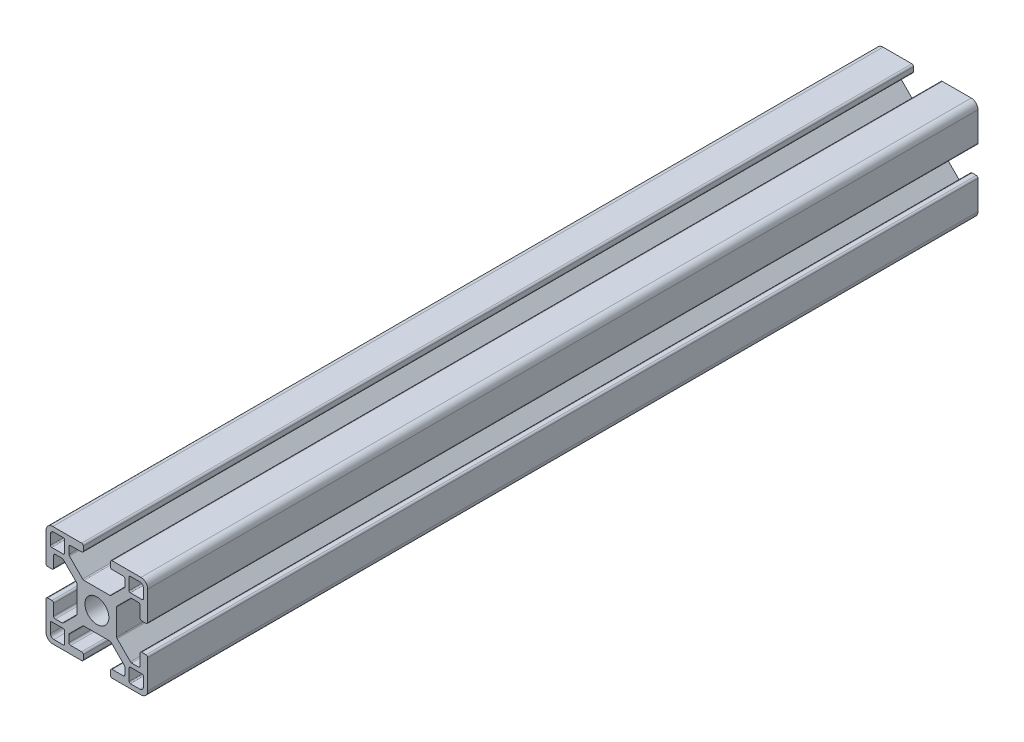
SolidWorks part; units mm, degrees
ref_plane "Front Plane" through (0, 0, 0) normal (0, 0, 1) x (1, 0, 0)
ref_plane "Top Plane" through (0, 0, 0) normal (0, 1, 0) x (1, 0, 0)
ref_plane "Right Plane" through (0, 0, 0) normal (1, 0, 0) x (0, 0, -1)
sketch "Sketch1" plane through (0, 0, 0) normal (0, 0, 1) x (1, 0, 0)
  line L0 (3.9799, -2.4733) -> (3.1981, -1.4942) construction
  line L1 (1.4942, -3.1981) -> (2.4733, -3.9799) construction
  line L2 (-2.4733, -3.9799) -> (-1.4942, -3.1981) construction
  line L3 (-3.1981, -1.4942) -> (-3.9799, -2.4733) construction
  line L4 (-3.9799, 2.4733) -> (-3.1981, 1.4942) construction
  line L5 (-1.4942, 3.1981) -> (-2.4733, 3.9799) construction
  line L6 (2.4733, 3.9799) -> (1.4942, 3.1981) construction
  line L7 (3.1981, 1.4942) -> (3.9799, 2.4733) construction
  line L8 (-12.6999, -13.6999) -> (-9.881, -13.6999)
  line L9 (-13.6999, -9.881) -> (-13.6999, -12.6999)
  line L10 (-9.88, -9.5) -> (-13.3189, -9.5)
  line L11 (-9.5, -13.3189) -> (-9.5, -9.88)
  line L12 (13.6999, -12.6999) -> (13.6999, -9.881)
  line L13 (9.881, -13.6999) -> (12.6999, -13.6999)
  line L14 (9.5, -9.88) -> (9.5, -13.3189)
  line L15 (13.3189, -9.5) -> (9.88, -9.5)
  line L16 (9.88, 9.5) -> (13.3189, 9.5)
  line L17 (9.5, 13.3189) -> (9.5, 9.88)
  line L18 (12.6999, 13.6999) -> (9.881, 13.6999)
  line L19 (13.6999, 9.881) -> (13.6999, 12.6999)
  line L20 (-13.6999, 12.6999) -> (-13.6999, 9.881)
  line L21 (-9.881, 13.6999) -> (-12.6999, 13.6999)
  line L22 (-9.5, 9.88) -> (-9.5, 13.3189)
  line L23 (-13.3189, 9.5) -> (-9.88, 9.5)
  line L24 (14.4999, -4) -> (13.2425, -4)
  line L25 (12.7425, -4.5) -> (12.7425, -7.7325)
  line L26 (12.2428, -8.25) -> (10.2602, -8.25)
  line L27 (9.9066, -8.1035) -> (5.9811, -4.178)
  line L28 (5.8347, -3.8245) -> (5.8347, -1.0125)
  line L29 (5.8347, -1.0125) -> (5.3247, -0.0625) construction
  line L30 (5.3247, -0.0625) -> (5.8347, 0.8875) construction
  line L31 (5.8347, 0.8875) -> (5.8347, 3.8245)
  line L32 (5.9811, 4.178) -> (9.9066, 8.1035)
  line L33 (10.2602, 8.25) -> (12.2428, 8.25)
  line L34 (12.7425, 7.7325) -> (12.7425, 4.5)
  line L35 (13.2425, 4) -> (14.4999, 4)
  line L36 (14.9999, 4.5) -> (14.9999, 12.9999)
  line L37 (12.9999, 14.9999) -> (4.5, 14.9999)
  line L38 (4, 14.4999) -> (4, 13.2425)
  line L39 (4.5, 12.7425) -> (7.7325, 12.7425)
  line L40 (8.25, 12.2428) -> (8.25, 10.2602)
  line L41 (8.1035, 9.9066) -> (4.178, 5.9811)
  line L42 (3.8245, 5.8347) -> (0.95, 5.8347)
  line L43 (0.95, 5.8347) -> (0, 5.3247) construction
  line L44 (0, 5.3247) -> (-0.95, 5.8347) construction
  line L45 (-0.95, 5.8347) -> (-3.8245, 5.8347)
  line L46 (-4.178, 5.9811) -> (-8.1035, 9.9066)
  line L47 (-8.25, 10.2602) -> (-8.25, 12.2428)
  line L48 (-7.7325, 12.7425) -> (-4.5, 12.7425)
  line L49 (-4, 13.2425) -> (-4, 14.4999)
  line L50 (-4.5, 14.9999) -> (-12.9999, 14.9999)
  line L51 (-14.9999, 12.9999) -> (-14.9999, 4.5)
  line L52 (-14.4999, 4) -> (-13.2425, 4)
  line L53 (-12.7425, 4.5) -> (-12.7425, 7.7325)
  line L54 (-12.2428, 8.25) -> (-10.2602, 8.25)
  line L55 (-9.9066, 8.1035) -> (-5.9811, 4.178)
  line L56 (-5.8347, 3.8245) -> (-5.8347, 0.8875)
  line L57 (-5.8347, 0.8875) -> (-5.3247, -0.0625) construction
  line L58 (-5.3247, -0.0625) -> (-5.8347, -1.0125) construction
  line L59 (-5.8347, -1.0125) -> (-5.8347, -3.8245)
  line L60 (-5.9811, -4.178) -> (-9.9066, -8.1035)
  line L61 (-10.2602, -8.25) -> (-12.2428, -8.25)
  line L62 (-12.7425, -7.7325) -> (-12.7425, -4.5)
  line L63 (-13.2425, -4) -> (-14.4999, -4)
  line L64 (-14.9999, -4.5) -> (-14.9999, -12.9999)
  line L65 (-12.9999, -14.9999) -> (-4.5, -14.9999)
  line L66 (-4, -14.4999) -> (-4, -13.2425)
  line L67 (-4.5, -12.7425) -> (-7.7325, -12.7425)
  line L68 (-8.25, -12.2428) -> (-8.25, -10.2602)
  line L69 (-8.1035, -9.9066) -> (-4.178, -5.9811)
  line L70 (-3.8245, -5.8347) -> (-0.95, -5.8347)
  line L71 (-0.95, -5.8347) -> (0, -5.3247) construction
  line L72 (0, -5.3247) -> (0.95, -5.8347) construction
  line L73 (0.95, -5.8347) -> (3.8245, -5.8347)
  line L74 (4.178, -5.9811) -> (8.1035, -9.9066)
  line L75 (8.25, -10.2602) -> (8.25, -12.2428)
  line L76 (7.7325, -12.7425) -> (4.5, -12.7425)
  line L77 (4, -13.2425) -> (4, -14.4999)
  line L78 (4.5, -14.9999) -> (12.9999, -14.9999)
  line L79 (14.9999, -12.9999) -> (14.9999, -4.5)
  line L80 (-5.8347, -1.0125) -> (-5.8347, 0.8875)
  line L81 (-0.95, 5.8347) -> (0.95, 5.8347)
  line L82 (5.8347, 0.8875) -> (5.8347, -1.0125)
  line L83 (-0.95, -5.8347) -> (0.95, -5.8347)
  arc A0 (2.4733, -3.9799) -> (3.9799, -2.4733) centre (3.1422, -3.1422) ccw construction
  arc A1 (-1.4942, -3.1981) -> (1.4942, -3.1981) centre (0, 0) ccw construction
  arc A2 (-3.9799, -2.4733) -> (-2.4733, -3.9799) centre (-3.1422, -3.1422) ccw construction
  arc A3 (-3.1981, 1.4942) -> (-3.1981, -1.4942) centre (0, 0) ccw construction
  arc A4 (-2.4733, 3.9799) -> (-3.9799, 2.4733) centre (-3.1422, 3.1422) ccw construction
  arc A5 (1.4942, 3.1981) -> (-1.4942, 3.1981) centre (0, 0) ccw construction
  arc A6 (3.9799, 2.4733) -> (2.4733, 3.9799) centre (3.1422, 3.1422) ccw construction
  arc A7 (3.1981, -1.4942) -> (3.1981, 1.4942) centre (0, 0) ccw construction
  arc A8 (-13.6999, -12.6999) -> (-12.6999, -13.6999) centre (-12.6999, -12.6999) ccw
  arc A9 (-13.3189, -9.5) -> (-13.6999, -9.881) centre (-13.3189, -9.881) ccw
  arc A10 (-9.5, -9.88) -> (-9.88, -9.5) centre (-9.88, -9.88) ccw
  arc A11 (-9.881, -13.6999) -> (-9.5, -13.3189) centre (-9.881, -13.3189) ccw
  arc A12 (12.6999, -13.6999) -> (13.6999, -12.6999) centre (12.6999, -12.6999) ccw
  arc A13 (9.5, -13.3189) -> (9.881, -13.6999) centre (9.881, -13.3189) ccw
  arc A14 (9.88, -9.5) -> (9.5, -9.88) centre (9.88, -9.88) ccw
  arc A15 (13.6999, -9.881) -> (13.3189, -9.5) centre (13.3189, -9.881) ccw
  arc A16 (9.5, 9.88) -> (9.88, 9.5) centre (9.88, 9.88) ccw
  arc A17 (9.881, 13.6999) -> (9.5, 13.3189) centre (9.881, 13.3189) ccw
  arc A18 (13.6999, 12.6999) -> (12.6999, 13.6999) centre (12.6999, 12.6999) ccw
  arc A19 (13.3189, 9.5) -> (13.6999, 9.881) centre (13.3189, 9.881) ccw
  arc A20 (14.9999, -4.5) -> (14.4999, -4) centre (14.4999, -4.5) ccw
  arc A21 (13.2425, -4) -> (12.7425, -4.5) centre (13.2425, -4.5) ccw
  arc A22 (12.2428, -8.25) -> (12.7425, -7.7325) centre (12.2428, -7.75) ccw
  arc A23 (9.9066, -8.1035) -> (10.2602, -8.25) centre (10.2602, -7.75) ccw
  arc A24 (5.8347, -3.8245) -> (5.9811, -4.178) centre (6.3347, -3.8245) ccw
  arc A25 (5.9811, 4.178) -> (5.8347, 3.8245) centre (6.3347, 3.8245) ccw
  arc A26 (10.2602, 8.25) -> (9.9066, 8.1035) centre (10.2602, 7.75) ccw
  arc A27 (12.7425, 7.7325) -> (12.2428, 8.25) centre (12.2428, 7.75) ccw
  arc A28 (12.7425, 4.5) -> (13.2425, 4) centre (13.2425, 4.5) ccw
  arc A29 (14.4999, 4) -> (14.9999, 4.5) centre (14.4999, 4.5) ccw
  arc A30 (14.9999, 12.9999) -> (12.9999, 14.9999) centre (12.9999, 12.9999) ccw
  arc A31 (4.5, 14.9999) -> (4, 14.4999) centre (4.5, 14.4999) ccw
  arc A32 (4, 13.2425) -> (4.5, 12.7425) centre (4.5, 13.2425) ccw
  arc A33 (8.25, 12.2428) -> (7.7325, 12.7425) centre (7.75, 12.2428) ccw
  arc A34 (8.1035, 9.9066) -> (8.25, 10.2602) centre (7.75, 10.2602) ccw
  arc A35 (3.8245, 5.8347) -> (4.178, 5.9811) centre (3.8245, 6.3347) ccw
  arc A36 (-4.178, 5.9811) -> (-3.8245, 5.8347) centre (-3.8245, 6.3347) ccw
  arc A37 (-8.25, 10.2602) -> (-8.1035, 9.9066) centre (-7.75, 10.2602) ccw
  arc A38 (-7.7325, 12.7425) -> (-8.25, 12.2428) centre (-7.75, 12.2428) ccw
  arc A39 (-4.5, 12.7425) -> (-4, 13.2425) centre (-4.5, 13.2425) ccw
  arc A40 (-4, 14.4999) -> (-4.5, 14.9999) centre (-4.5, 14.4999) ccw
  arc A41 (-12.9999, 14.9999) -> (-14.9999, 12.9999) centre (-12.9999, 12.9999) ccw
  arc A42 (-14.9999, 4.5) -> (-14.4999, 4) centre (-14.4999, 4.5) ccw
  arc A43 (-13.2425, 4) -> (-12.7425, 4.5) centre (-13.2425, 4.5) ccw
  arc A44 (-12.2428, 8.25) -> (-12.7425, 7.7325) centre (-12.2428, 7.75) ccw
  arc A45 (-9.9066, 8.1035) -> (-10.2602, 8.25) centre (-10.2602, 7.75) ccw
  arc A46 (-5.8347, 3.8245) -> (-5.9811, 4.178) centre (-6.3347, 3.8245) ccw
  arc A47 (-5.9811, -4.178) -> (-5.8347, -3.8245) centre (-6.3347, -3.8245) ccw
  arc A48 (-10.2602, -8.25) -> (-9.9066, -8.1035) centre (-10.2602, -7.75) ccw
  arc A49 (-12.7425, -7.7325) -> (-12.2428, -8.25) centre (-12.2428, -7.75) ccw
  arc A50 (-12.7425, -4.5) -> (-13.2425, -4) centre (-13.2425, -4.5) ccw
  arc A51 (-14.4999, -4) -> (-14.9999, -4.5) centre (-14.4999, -4.5) ccw
  arc A52 (-14.9999, -12.9999) -> (-12.9999, -14.9999) centre (-12.9999, -12.9999) ccw
  arc A53 (-4.5, -14.9999) -> (-4, -14.4999) centre (-4.5, -14.4999) ccw
  arc A54 (-4, -13.2425) -> (-4.5, -12.7425) centre (-4.5, -13.2425) ccw
  arc A55 (-8.25, -12.2428) -> (-7.7325, -12.7425) centre (-7.75, -12.2428) ccw
  arc A56 (-8.1035, -9.9066) -> (-8.25, -10.2602) centre (-7.75, -10.2602) ccw
  arc A57 (-3.8245, -5.8347) -> (-4.178, -5.9811) centre (-3.8245, -6.3347) ccw
  arc A58 (4.178, -5.9811) -> (3.8245, -5.8347) centre (3.8245, -6.3347) ccw
  arc A59 (8.25, -10.2602) -> (8.1035, -9.9066) centre (7.75, -10.2602) ccw
  arc A60 (7.7325, -12.7425) -> (8.25, -12.2428) centre (7.75, -12.2428) ccw
  arc A61 (4.5, -12.7425) -> (4, -13.2425) centre (4.5, -13.2425) ccw
  arc A62 (4, -14.4999) -> (4.5, -14.9999) centre (4.5, -14.4999) ccw
  arc A63 (12.9999, -14.9999) -> (14.9999, -12.9999) centre (12.9999, -12.9999) ccw
  arc A64 (-12.6999, 13.6999) -> (-13.6999, 12.6999) centre (-12.6999, 12.6999) ccw
  arc A65 (-9.5, 13.3189) -> (-9.881, 13.6999) centre (-9.881, 13.3189) ccw
  arc A66 (-9.88, 9.5) -> (-9.5, 9.88) centre (-9.88, 9.88) ccw
  arc A67 (-13.6999, 9.881) -> (-13.3189, 9.5) centre (-13.3189, 9.881) ccw
  circle A68 centre (0, 0) radius 3.53
extrude "Boss-Extrude1" add sketch "Sketch1" along normal mid plane 244.7923
